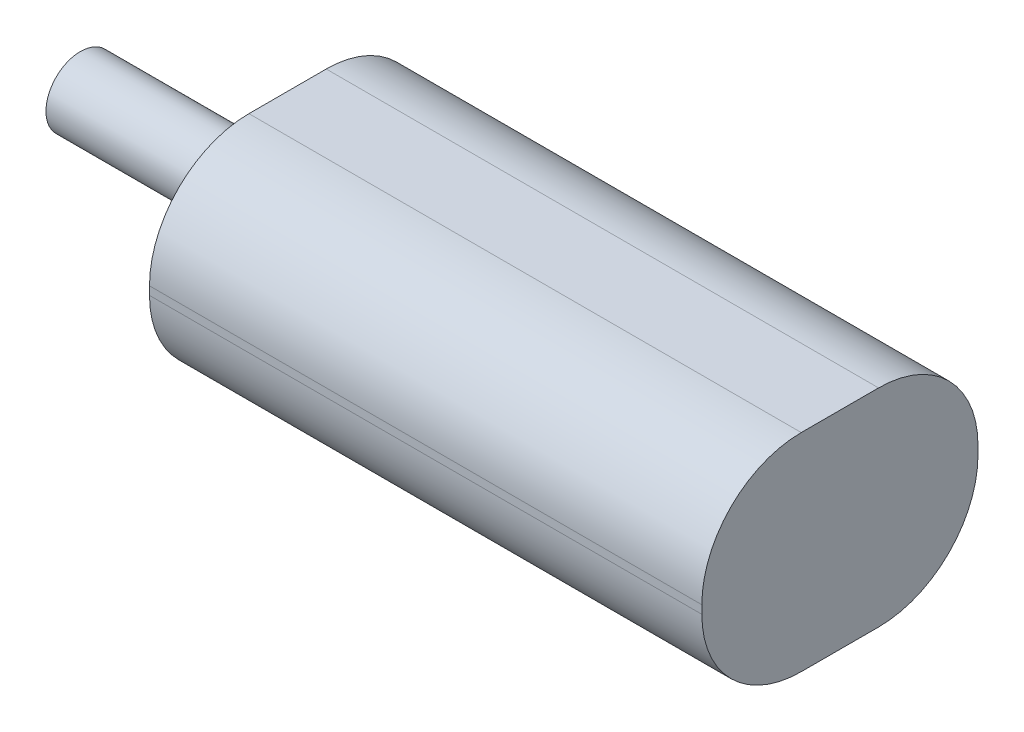
SolidWorks part; units mm, degrees
ref_plane "Front Plane" through (0, 0, 0) normal (0, 0, 1) x (1, 0, 0)
ref_plane "Top Plane" through (0, 0, 0) normal (0, 1, 0) x (1, 0, 0)
ref_plane "Right Plane" through (0, 0, 0) normal (1, 0, 0) x (0, 0, -1)
sketch "Sketch1" plane through (0, 0, 0) normal (0, 1, 0) x (1, 0, 0)
  line L1 (0, 0) -> (25.4, 0)
  line L2 (0, 0) -> (0, 12.7)
  line L3 (0, 12.7) -> (25.4, 12.7)
  line L4 (25.4, 0) -> (25.4, 12.7)
  dimension "D1" = 25.4
  dimension "D2" = 12.7
extrude "Boss-Extrude1" add sketch "Sketch1" along normal blind 9.525
sketch "Sketch2" plane through (0, 0, 0) normal (-1, 0, 0) x (0, 0, 1)
  circle A0 centre (-6.35, 4.7625) radius 1.5875
  dimension "D1" = 3.175
extrude "Boss-Extrude2" add sketch "Sketch2" along normal blind 9.525
fillet "Fillet1" radius 4.572 4 edges at (12.7, 0, 0) (12.7, 0, -12.7) (12.7, 9.525, -12.7) (12.7, 9.525, 0)
